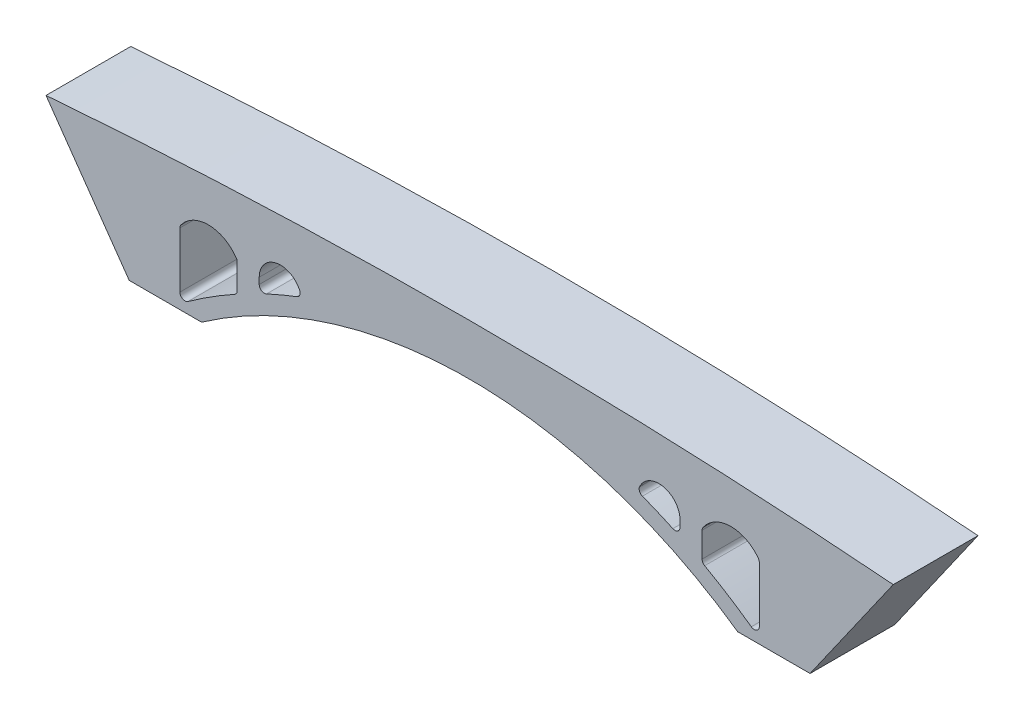
SolidWorks part; units mm, degrees
ref_plane "前视基准面" through (0, 0, 0) normal (0, 0, 1) x (1, 0, 0)
ref_plane "上视基准面" through (0, 0, 0) normal (0, 1, 0) x (1, 0, 0)
ref_plane "右视基准面" through (0, 0, 0) normal (1, 0, 0) x (0, 0, -1)
sketch "草图2" plane through (0, 0, 0) normal (0, 0, 1) x (1, 0, 0)
  line L0 (175, 0) -> (-175, 0) construction
  line L1 (0, 0) -> (0, 60) construction
  line L2 (250, 70) -> (-250, 70) construction
  line L3 (0, 60) -> (0, 80) construction
  line L4 (-175, 0) -> (-200.8987, 0)
  line L5 (-200.8987, 0) -> (-250, 70)
  line L6 (-137.1723, 42.2253) -> (-137.1723, 24.8468)
  line L7 (-170.9658, 42.7228) -> (-170.9658, 3.0777)
  line L8 (-124.1723, 40.0013) -> (-124.1723, 31.5504)
  line L9 (124.1723, 40.0013) -> (124.1723, 31.5504)
  line L10 (137.1723, 42.2253) -> (137.1723, 24.8468)
  line L11 (170.9658, 42.7228) -> (170.9658, 3.0777)
  line L12 (175, 0) -> (200.8987, 0)
  line L13 (200.8987, 0) -> (250, 70)
  line L14 (-175, 0) -> (-158.1798, 0)
  line L15 (158.1798, 0) -> (175, 0)
  arc A0 (-175, 0) -> (175, 0) centre (0, -225.2083) cw
  arc A1 (-250, 70) -> (250, 70) centre (0, -3050) cw
  arc A2 (-137.1723, 42.2253) -> (-170.9658, 42.7228) centre (-154.2265, 31.7777) ccw
  arc A3 (-99.3557, 42.1346) -> (-124.1723, 40.0013) centre (-111.6723, 40.0013) ccw
  arc A4 (-158.1798, 0) -> (158.1798, 0) centre (0, -225.2083) cw
  arc A5 (99.3557, 42.1346) -> (124.1723, 40.0013) centre (111.6723, 40.0013) cw
  arc A6 (-168.8641, -7.8963) -> (168.8641, -7.8963) centre (0, -225.2083) cw construction
  arc A7 (137.1723, 42.2253) -> (170.9658, 42.7228) centre (154.2265, 31.7777) cw
  point P4 (0, 0)
  point P9 (0, 70)
  point P12 (-200.4728, 0)
  point P38 (-302.8186, 0)
  point P39 (-200.8987, 0)
  dimension "D5" = 40
  dimension "D6" = 25
  dimension "D1" = 350
  dimension "D2" = 60
  dimension "D3" = 20
  dimension "D4" = 500
  dimension "D7" = 13
  dimension "D8" = 10
extrude "凸台-拉伸1" add sketch "草图2" along normal blind 50 contours L10 A7 L11 A0 L12 L13 A1 L5 L4 L7 A2 L6 L8 A3 A5 L9 | L14 A4 L15 A0
fillet "圆角1" radius 3 12 edges at (170.9658, 3.0777, 25) (137.1723, 24.8468, 25) (170.9658, 42.7228, 25) (137.1723, 42.2253, 25) (124.1723, 31.5504, 25) (99.3557, 42.1346, 25) (-99.3557, 42.1346, 25) (-124.1723, 31.5504, 25) (-137.1723, 24.8468, 25) (-137.1723, 42.2253, 25) (-170.9658, 42.7228, 25) (-170.9658, 3.0777, 25)
